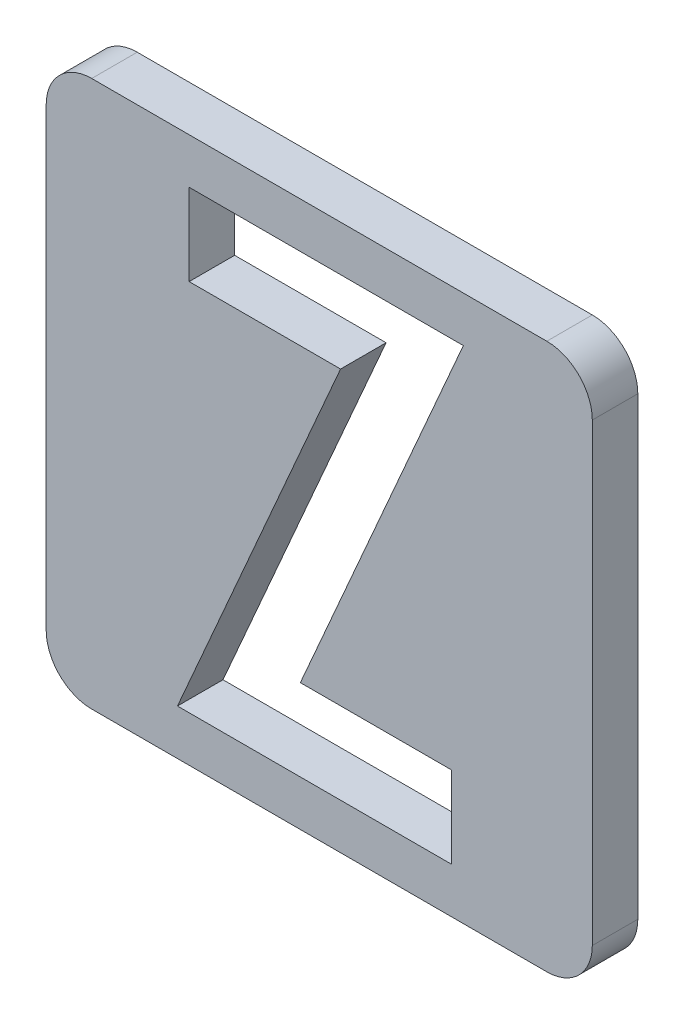
SolidWorks part; units mm, degrees
ref_plane "Front Plane" through (0, 0, 0) normal (0, 0, 1) x (1, 0, 0)
ref_plane "Top Plane" through (0, 0, 0) normal (0, 1, 0) x (1, 0, 0)
ref_plane "Right Plane" through (0, 0, 0) normal (1, 0, 0) x (0, 0, -1)
sketch "Sketch1" plane through (0, 0, 0) normal (0, 0, 1) x (1, 0, 0)
  line L1 (-50, 60) -> (50, 60)
  line L2 (-60, 50) -> (-60, -50)
  line L3 (-50, -60) -> (50, -60)
  line L4 (60, 50) -> (60, -50)
  line L5 (-60, 60) -> (60, -60) construction
  line L6 (-60, -60) -> (60, 60) construction
  arc A0 (-60, -50) -> (-50, -60) centre (-50, -50) ccw
  arc A1 (50, -60) -> (60, -50) centre (50, -50) ccw
  arc A2 (50, 60) -> (60, 50) centre (50, 50) cw
  arc A3 (-50, 60) -> (-60, 50) centre (-50, 50) ccw
  point P0 (0, 0)
  dimension "D3" = 10
  dimension "D1" = 120
  dimension "D2" = 120
extrude "Boss-Extrude1" add sketch "Sketch1" along normal blind 10 contours A3 L2 A0 L3 A1 L4 A2 L1
sketch "Sketch2" plane through (0, 0, 10) normal (0, 0, 1) x (1, 0, 0)
  line L0 (0, 0) -> (0, 40) construction
  line L1 (-50, 50) -> (50, 50) construction
  line L2 (-50, 50) -> (-50, -50) construction
  line L3 (-50, -50) -> (50, -50) construction
  line L4 (50, 50) -> (50, -50) construction
  line L5 (-50, 50) -> (50, -50) construction
  line L6 (-50, -50) -> (50, 50) construction
  line L7 (0, 40) -> (-40, 40) construction
  line L8 (-40, 40) -> (-40, 0) construction
  line L9 (-40, 0) -> (0, 0) construction
  line L11 (0, 20) -> (-20, 20) construction
  line L12 (-20, 40) -> (-20, 20) construction
  circle A0 centre (0, 40) radius 4 construction
  circle A1 centre (0, 20) radius 4 construction
  circle A2 centre (0, 0) radius 4 construction
  circle A3 centre (-20, 20) radius 4 construction
  circle A4 centre (-20, 40) radius 4 construction
  circle A5 centre (-40, 40) radius 4 construction
  circle A6 centre (0, 0) radius 4 construction
  circle A7 centre (20, 0) radius 4 construction
  circle A8 centre (40, 0) radius 4 construction
  circle A9 centre (40, 20) radius 4 construction
  circle A10 centre (40, 40) radius 4 construction
  circle A11 centre (20, 20) radius 4 construction
  circle A12 centre (0, 0) radius 4 construction
  circle A13 centre (0, -20) radius 4 construction
  circle A14 centre (0, -40) radius 4 construction
  circle A15 centre (20, -40) radius 4 construction
  circle A16 centre (40, -40) radius 4 construction
  circle A17 centre (20, -20) radius 4 construction
  circle A18 centre (0, 0) radius 4 construction
  circle A19 centre (-20, 0) radius 4 construction
  circle A20 centre (-40, 0) radius 4 construction
  circle A21 centre (-40, -20) radius 4 construction
  circle A22 centre (-40, -40) radius 4 construction
  circle A23 centre (-20, -20) radius 4 construction
  text T0 "Z" font "Century Gothic" height 100
  point P0 (0, 0)
  point P55 (0, 0)
  dimension "D4" = 8
  dimension "D1" = 100
  dimension "D2" = 100
  dimension "D3" = 40
  dimension "D5" = 4
extrude "Cut-Extrude39" cut sketch "Sketch2" against normal blind 10
